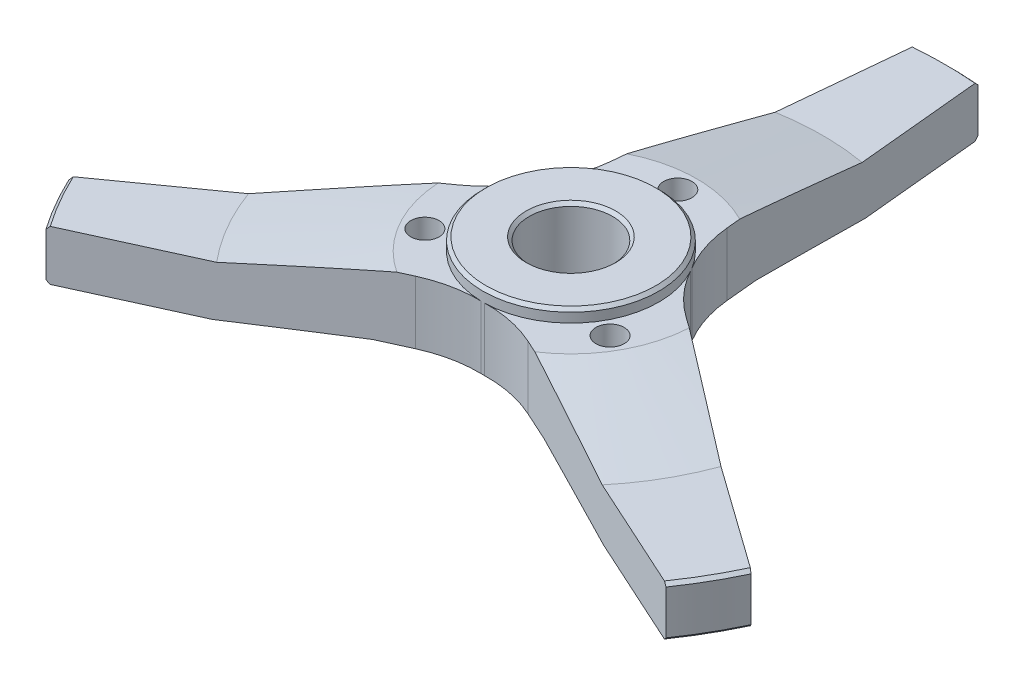
SolidWorks part; units mm, degrees
material "40Cr"
ref_plane "前视基准面" through (0, 0, 0) normal (0, 0, 1) x (1, 0, 0)
ref_plane "上视基准面" through (0, 0, 0) normal (0, 1, 0) x (1, 0, 0)
ref_plane "右视基准面" through (0, 0, 0) normal (1, 0, 0) x (0, 0, -1)
sketch "草图3" plane through (0, 0, 0) normal (0, 0, 1) x (1, 0, 0)
  line L0 (0, 0) -> (0, -128.4335) construction
  line L1 (0, 0) -> (-28, 0)
  line L2 (-28, 0) -> (-28, -4)
  line L3 (-28, -4) -> (-40, -4)
  line L4 (-40, -4) -> (-80, -12)
  line L5 (-80, -12) -> (-120, -12)
  line L6 (-120, -12) -> (-120, -28)
  line L7 (-120, -28) -> (-81, -28)
  line L8 (-81, -28) -> (-45, -24)
  line L9 (-45, -24) -> (0, -24)
  line L10 (0, -24) -> (0, 0)
  dimension "D1" = 28
  dimension "D2" = 4
  dimension "D3" = 12
  dimension "D4" = 8
  dimension "D5" = 120
  dimension "D6" = 80
  dimension "D7" = 16
  dimension "D8" = 39
  dimension "D9" = 45
  dimension "D10" = 4
revolve "旋转1" add sketch "草图3" angle 360 about L0
sketch "草图4" plane through (0, 0, 0) normal (0, 1, 0) x (1, 0, 0)
  line L0 (0, 0) -> (0, 120) construction
  line L1 (0, 0) -> (103.923, -60) construction
  line L2 (0, 0) -> (-103.923, -60) construction
  line L3 (-18.4068, 31.2963) -> (-9.905, 119.5905)
  line L4 (18.4068, 31.2963) -> (9.905, 119.5905)
  line L5 (17.9, -31.5889) -> (98.6159, -68.3732)
  line L6 (36.3068, 0.2926) -> (108.5209, -51.2173)
  line L7 (-36.3068, 0.2926) -> (-108.5209, -51.2173)
  line L8 (-17.9, -31.5889) -> (-98.6159, -68.3732)
  circle A0 centre (0, 0) radius 28 construction
  circle A1 centre (0, 0) radius 120 construction
  arc A2 (-23.974, 14.4654) -> (-24.5144, 13.5294) centre (0, 0) ccw
  circle A3 centre (0, 0) radius 28 construction
  arc A4 (24.5144, 13.5294) -> (23.974, 14.4654) centre (0, 0) ccw
  arc A5 (-0.5404, -27.9948) -> (0.5404, -27.9948) centre (0, 0) ccw
  arc A6 (0.5404, -27.9948) -> (17.9, -31.5889) centre (1.3123, -67.9873) cw
  arc A7 (-0.5404, -27.9948) -> (-17.9, -31.5889) centre (-1.3123, -67.9873) ccw
  arc A8 (24.5144, 13.5294) -> (36.3068, 0.2926) centre (59.5349, 32.8572) ccw
  arc A9 (23.974, 14.4654) -> (18.4068, 31.2963) centre (58.2226, 35.1302) cw
  arc A10 (-24.5144, 13.5294) -> (-36.3068, 0.2926) centre (-59.5349, 32.8572) cw
  arc A11 (-18.4068, 31.2963) -> (-23.974, 14.4654) centre (-58.2226, 35.1302) cw
  arc A12 (-108.5209, -51.2173) -> (-98.6159, -68.3732) centre (0, 0) ccw
  arc A13 (9.905, 119.5905) -> (-9.905, 119.5905) centre (0, 0) ccw
  arc A14 (98.6159, -68.3732) -> (108.5209, -51.2173) centre (0, 0) ccw
  point P5 (0, 0)
  point P14 (0, 0)
  point P16 (7.673, -26.9282)
  point P17 (0, 0)
  point P20 (0, 0)
  point P31 (0, 0)
  point P34 (-7.673, -26.9282)
  point P37 (27.157, 6.8191)
  point P40 (19.484, 20.1091)
  point P43 (-27.157, 6.8191)
  point P46 (-19.484, 20.1091)
  dimension "D6" = 40
  dimension "D1" = 120
  dimension "D2" = 120
  dimension "D3" = 19.81
  dimension "D4" = 11
  dimension "D5" = 3
extrude "切除-拉伸1" cut sketch "草图4" against normal up to surface (28 mm away) flip side to cut up to face at (0, -28, 81)
sketch "草图7" plane through (0, -24, 0) normal (0, -1, 0) x (1, 0, 0)
  line L0 (0, 0) -> (0, -120) construction
  line L1 (0, 0) -> (103.923, 60) construction
  line L2 (0, 0) -> (-103.923, 60) construction
  circle A0 centre (0, 0) radius 34 construction
  arc A1 (-9.905, -119.5905) -> (9.905, -119.5905) centre (0, 0) ccw construction
  arc A2 (108.5209, 51.2173) -> (98.6159, 68.3732) centre (0, 0) ccw construction
  arc A3 (-98.6159, 68.3732) -> (-108.5209, 51.2173) centre (0, 0) ccw construction
  dimension "D1" = 68
hole_wizard "打孔尺寸(%根据)内六角圆柱头螺钉的类型1" positions "3D草图1" profile "草图8" counterbore size "M8" standard "GB" end condition up to next
sketch3d "3D草图1"
  line L0 (0, -24, 0) -> (0, -24, -120) construction
  line L1 (0, -24, 0) -> (103.923, -24, 60) construction
  line L2 (0, -24, 0) -> (-103.923, -24, 60) construction
  circle A0 centre (0, -24, 0) radius 34 construction
  point P0 (0, -24, -34)
  point P6 (0, -58, 0)
  point P7 (29.4449, -24, 17)
  point P11 (-29.4449, -24, 17)
sketch "草图8" plane through (0, -24, -34) normal (1, 0, 0) x (0, 0, -1)
  line L0 (0, 0) -> (0, 20)
  line L1 (0, 20) -> (4.5, 20)
  line L3 (4.5, 20) -> (4.5, 9)
  line L4 (4.5, 9) -> (7.5, 9)
  line L5 (7.5, 9) -> (7.5, 0)
  line L7 (7.5, 0) -> (0, 0)
  line L11 (0, -6.35) -> (0, 107.95) construction
  dimension "通孔孔直径" = 9
  dimension "通孔孔深度" = 20
  dimension "柱形沉头孔直径" = 15
  dimension "柱形沉头孔深度" = 9
sketch "草图9" plane through (0, 0, 0) normal (0, 1, 0) x (1, 0, 0)
  circle A0 centre (0, 0) radius 15
  dimension "D1" = 30
hole_wizard "M30 螺纹孔2" positions "3D草图6" profile "草图14" tap size "M30" standard "GB" end condition up to next
sketch3d "3D草图6"
  point P0 (0, 0, 0)
  dimension "D1" = 0
sketch "草图14" plane through (0, 0, 0) normal (1, 0, 0) x (0, 0, 1)
  line L0 (0, 0) -> (0, 24)
  line L1 (0, 24) -> (13.25, 24)
  line L2 (13.25, 24) -> (13.25, 0)
  line L5 (13.25, 0) -> (0, 0)
  line L11 (0, -6.35) -> (0, 107.95) construction
  dimension "通孔螺纹孔钻头直径" = 26.5
  dimension "通孔螺纹孔钻头深度" = 24
cosmetic thread "孔螺蚊线2" parameters "D2"=30
chamfer "倒角1" distance 1 angle 45 9 edges at (0, 0, 28) (0, 0, 13.25) (0, -24, -13.25) (0, -28, -120) (-103.923, -28, 60) (0, -12, -120) (-103.923, -12, 60) (103.923, -28, 60) (103.923, -12, 60)
